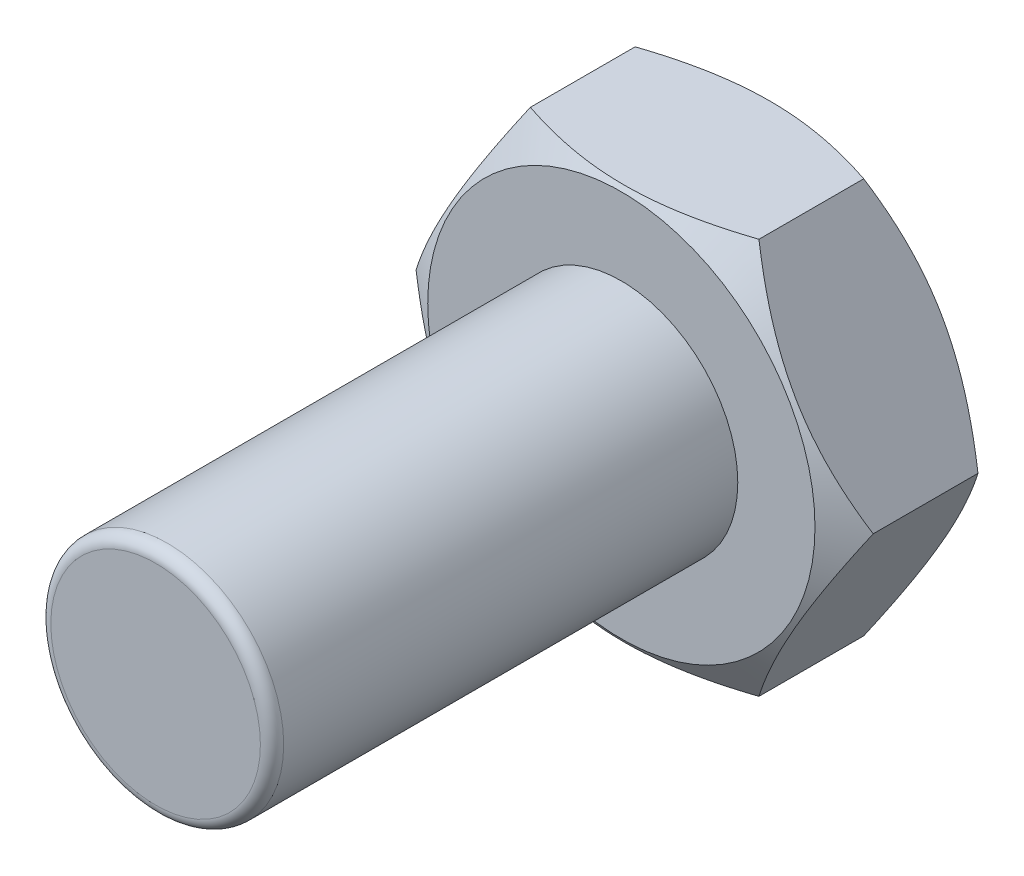
SolidWorks part; units mm, degrees
material "1.0036 (S235JRG1)"
ref_plane "Ön Düzlem" through (0, 0, 0) normal (0, 0, 1) x (1, 0, 0)
ref_plane "Üst Düzlem" through (0, 0, 0) normal (0, 1, 0) x (1, 0, 0)
ref_plane "Sağ Düzlem" through (0, 0, 0) normal (1, 0, 0) x (0, 0, -1)
sketch "Çizim1" plane through (0, 0, 0) normal (0, 0, 1) x (1, 0, 0)
  line L1 (9.815, 0) -> (4.9075, 8.5)
  line L2 (4.9075, 8.5) -> (-4.9075, 8.5)
  line L3 (-4.9075, 8.5) -> (-9.815, 0)
  line L4 (-9.815, 0) -> (-4.9075, -8.5)
  line L5 (-4.9075, -8.5) -> (4.9075, -8.5)
  line L6 (4.9075, -8.5) -> (9.815, 0)
  circle A0 centre (0, 0) radius 8.5 construction
  dimension "D1" = 17
extrude "Yükseklik-Ekstrüzyon1" add sketch "Çizim1" along normal blind 6.5
sketch "Çizim2" plane through (0, 0, 6.5) normal (0, 0, 1) x (1, 0, 0)
  circle A0 centre (0, 0) radius 5
  dimension "D1" = 10
extrude "Yükseklik-Ekstrüzyon2" add sketch "Çizim2" along normal blind 20
cosmetic thread "Kozmetik Diş Açma1" parameters "D2"=8.344
sketch "Çizim3" plane through (0, 0, 0) normal (0, 1, 0) x (1, 0, 0)
  line L0 (-9.815, 0) -> (-8.315, 0)
  line L1 (-4.9075, 0) -> (-9.815, 0) construction
  line L2 (-8.315, 0) -> (-9.815, -1)
  line L3 (-9.815, -6.5) -> (-9.815, 0) construction
  line L4 (-9.815, -1) -> (-9.815, 0)
  line L9 (-9.815, -6.5) -> (-9.815, -5.5)
  line L10 (-9.815, -5.5) -> (-8.315, -6.5)
  line L11 (-4.9075, -6.5) -> (-9.815, -6.5) construction
  line L12 (-8.315, -6.5) -> (-9.815, -6.5)
  line L13 (0, 0) -> (0, -6.5) construction
  line L14 (-5, -6.5) -> (5, -6.5) construction
  dimension "D1" = 1.5
  dimension "D2" = 1
  dimension "D3" = 1
  dimension "D4" = 1.5
revolve "Kes-Döndür1" cut sketch "Çizim3" angle 360 about L13
fillet "Radyus1" radius 0.5 1 edges at (5, 0, 26.5)
